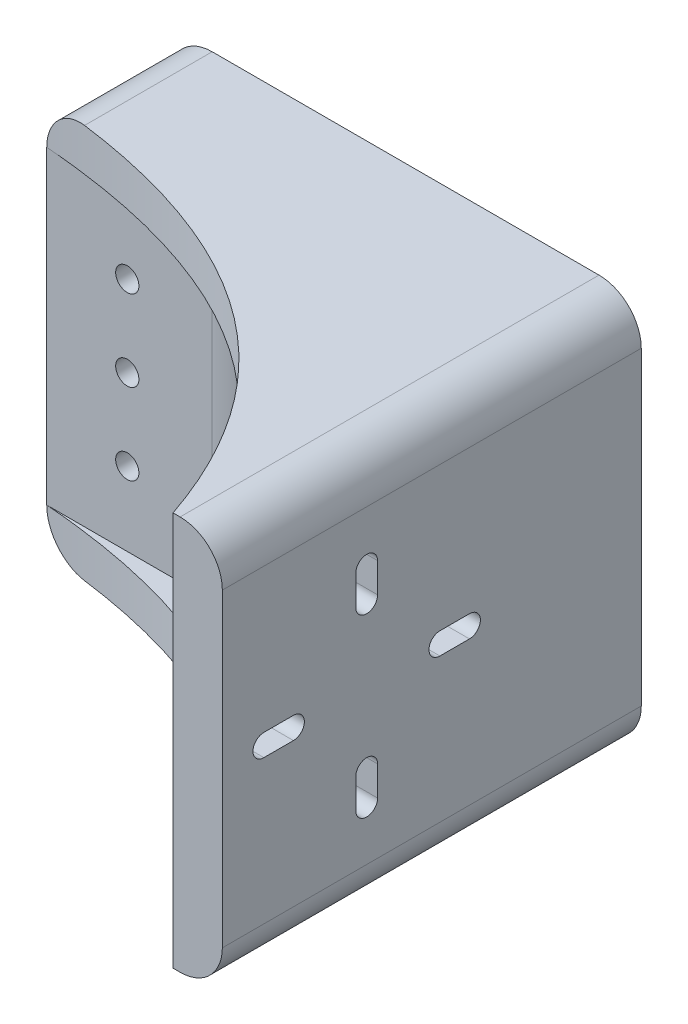
SolidWorks part; units mm, degrees
ref_plane "Plano frontal" through (0, 0, 0) normal (0, 0, 1) x (1, 0, 0)
ref_plane "Plano superior" through (0, 0, 0) normal (0, 1, 0) x (1, 0, 0)
ref_plane "Plano direito" through (0, 0, 0) normal (1, 0, 0) x (0, 0, -1)
sketch "Esboço1" plane through (0, 0, 0) normal (0, 0, 1) x (1, 0, 0)
  line L1 (-30.7631, 20.254) -> (36.1769, 20.254)
  line L2 (-30.7631, 20.254) -> (-30.7631, -19.746)
  line L3 (-30.7631, -19.746) -> (36.1769, -19.746)
  line L4 (36.1769, 20.254) -> (36.1769, -19.746)
  line L5 (2.7069, -19.746) -> (2.7069, 20.254) construction
  line L6 (-30.7631, 0.254) -> (36.1769, 0.254) construction
  point P424 (2.7069, 0.254)
  dimension "D1" = 40
  dimension "D2" = 66.94
extrude "Ressalto-extrusão1" add sketch "Esboço1" along normal blind 9.5
sketch "Esboço2" plane through (0, 0, 9.5) normal (0, 0, 1) x (1, 0, 0)
  line L5 (-30.7631, -19.746) -> (36.1769, -19.746) construction
  line L6 (29.1769, -19.746) -> (36.1769, -19.746)
  line L7 (29.1769, -19.746) -> (29.1769, 20.254)
  line L8 (29.1769, 20.254) -> (36.1769, 20.254)
  line L9 (36.1769, -19.746) -> (36.1769, 20.254)
  line L10 (32.6769, 20.254) -> (32.6769, -19.746) construction
  line L11 (29.1769, 0.254) -> (36.1769, 0.254) construction
  point P509 (32.6769, 0.254)
  dimension "D1" = 7
extrude "Ressalto-extrusão2" add sketch "Esboço2" along normal blind 50
sketch "Esboço3" plane through (0, 0, 9.5) normal (0, 0, 1) x (1, 0, 0)
  line L1 (-30.7631, -19.746) -> (-30.7631, 20.254)
  line L2 (-2.3231, 20.254) -> (-30.7631, 20.254)
  line L3 (-2.3231, -19.746) -> (-2.3231, 20.254)
  line L4 (-30.7631, -19.746) -> (-2.3231, -19.746)
  line L5 (-2.3231, 0.254) -> (-30.7631, 0.254) construction
  dimension "D2" = 28.44
  dimension "D3" = 40
extrude "Ressalto-extrusão3" add sketch "Esboço3" along normal blind 8
ref_plane "Plano1" through (0, 0.254, 0) normal (0, 1, 0) x (1, 0, 0)
sketch "Esboço4" plane through (0, -19.746, 0) normal (0, -1, 0) x (1, 0, 0)
  line L8 (-30.7631, 0) -> (36.1769, 0)
  line L9 (36.1769, 0) -> (36.1769, 59.5)
  line L10 (36.1769, 59.5) -> (29.1769, 59.5)
  line L11 (29.1769, 59.5) -> (29.1769, 9.5)
  line L12 (29.1769, 9.5) -> (-2.3231, 9.5)
  line L13 (-2.3231, 9.5) -> (-2.3231, 17.5)
  line L14 (-2.3231, 9.5) -> (-2.3231, 17.5)
  line L15 (-30.7631, 17.5) -> (-30.7631, 0)
  line L16 (-30.7631, 0) -> (36.1769, 0)
  line L17 (36.1769, 0) -> (36.1769, 59.5)
  line L18 (36.1769, 59.5) -> (29.1769, 59.5)
  line L19 (29.1769, 59.5) -> (29.1769, 9.5)
  line L20 (29.1769, 9.5) -> (-2.3231, 9.5)
  line L23 (-30.7631, 17.5) -> (-30.7631, 0)
  line L24 (-2.3231, 17.5) -> (-30.7631, 17.5)
  line L25 (-2.3231, 17.5) -> (-30.7631, 17.5)
  dimension "D1" = 0
extrude "Ressalto-extrusão4" add sketch "Esboço4" along normal blind 2 contours L16 L17 L18 L19 L20 L14 L25 L23
mirror "Espelhar1" about plane through (0, 0.254, 0) normal (0, 1, 0) of "Ressalto-extrusão4"
sketch "Esboço5" plane through (0, -21.746, 0) normal (0, -1, 0) x (1, 0, 0)
  line L8 (-30.7631, 17.5) -> (-30.7631, 0)
  line L9 (-30.7631, 0) -> (36.1769, 0)
  line L10 (36.1769, 0) -> (36.1769, 59.5)
  line L11 (36.1769, 59.5) -> (29.1769, 59.5)
  line L12 (29.1769, 59.5) -> (29.1769, 9.5)
  line L13 (29.1769, 9.5) -> (-2.3231, 9.5)
  line L14 (-2.3231, 9.5) -> (-2.3231, 17.5)
  line L15 (-2.3231, 9.5) -> (-2.3231, 17.5)
  line L16 (-30.7631, 17.5) -> (-30.7631, 0)
  line L17 (-30.7631, 0) -> (36.1769, 0)
  line L18 (36.1769, 0) -> (36.1769, 59.5)
  line L19 (36.1769, 59.5) -> (29.1769, 59.5)
  line L20 (29.1769, 59.5) -> (29.1769, 9.5)
  line L24 (-2.3231, 17.5) -> (-30.7631, 17.5)
  line L25 (-2.3231, 17.5) -> (-30.7631, 17.5)
  spline S0 degree 2 poles (29.1769, 59.5) (16.1631, 21.1433) (-30.7631, 17.5) knots 0 0 0 1 1 1
  dimension "D1" = 0
extrude "Ressalto-extrusão5" add sketch "Esboço5" along normal blind 6
mirror "Espelhar2" about plane through (0, 0.254, 0) normal (0, 1, 0) of "Ressalto-extrusão5"
fillet "Filete1" radius 5 1 edges at (-2.3231, 0.254, 17.5)
fillet "Filete2" radius 20 1 edges at (29.1769, 0.254, 9.5)
sketch "Esboço6" plane through (0, 0, 17.5) normal (0, 0, 1) x (1, 0, 0)
  line L4 (-30.7631, -21.746) -> (-7.3231, -21.746)
  line L5 (-7.3231, -21.746) -> (-7.3231, 22.254)
  line L6 (-7.3231, 22.254) -> (-30.7631, 22.254)
  line L7 (-30.7631, 22.254) -> (-30.7631, -21.746)
  line L8 (-30.7631, -21.746) -> (-7.3231, -21.746)
  line L9 (-7.3231, -21.746) -> (-7.3231, 22.254)
  line L10 (-7.3231, 22.254) -> (-30.7631, 22.254)
  line L11 (-30.7631, 22.254) -> (-30.7631, -21.746)
  circle A0 centre (-19.3231, 0.254) radius 3.625 construction
  circle A1 centre (-19.3231, 0.254) radius 3.625 construction
  circle A2 centre (-19.3231, -11.246) radius 3.625 construction
  circle A3 centre (-19.3231, -11.246) radius 3.625 construction
  circle A4 centre (-19.3231, 11.754) radius 3.625 construction
  circle A5 centre (-19.3231, 11.754) radius 3.625 construction
  circle A6 centre (-19.3231, 11.754) radius 1.65
  circle A7 centre (-19.3231, 0.254) radius 1.65
  circle A8 centre (-19.3231, -11.246) radius 1.65
  dimension "D2" = 3.3
  dimension "D1" = 0
extrude "Corte-extrusão1" cut sketch "Esboço6" against normal through all contours A6 | A7 | A8
sketch "Esboço7" plane through (0, 0, 0) normal (0, 0, -1) x (-1, 0, 0)
  line L0 (19.3231, 11.754) -> (19.3231, -11.246) construction
  line L1 (27.3231, 11.754) -> (27.3231, -11.246)
  line L2 (11.3231, 11.754) -> (11.3231, -11.246)
  arc A0 (27.3231, 11.754) -> (11.3231, 11.754) centre (19.3231, 11.754) ccw
  arc A1 (11.3231, -11.246) -> (27.3231, -11.246) centre (19.3231, -11.246) ccw
  point P2 (19.3231, 0.254)
  dimension "D1" = 8
extrude "Corte-extrusão2" cut sketch "Esboço7" against normal blind 8
fillet "Filete4" radius 6 4 edges at (36.1769, -27.746, 29.75) (36.1769, 28.254, 29.75) (-30.7631, 28.254, 8.75) (-30.7631, -27.746, 8.75)
sketch "Esboço8" plane through (36.1769, 0, 0) normal (1, 0, 0) x (0, 0, -1)
  line L0 (-39, 0.254) -> (-51.5, 0.254) construction
  line L1 (-53.6, 0.254) -> (-49.4, 0.254) construction
  line L2 (-53.6, 1.804) -> (-49.4, 1.804)
  line L3 (-53.6, -1.296) -> (-49.4, -1.296)
  line L4 (-39, -14.346) -> (-39, -10.146) construction
  line L5 (-40.55, -14.346) -> (-40.55, -10.146)
  line L6 (-37.45, -14.346) -> (-37.45, -10.146)
  line L7 (-24.4, 0.254) -> (-28.6, 0.254) construction
  line L8 (-24.4, -1.296) -> (-28.6, -1.296)
  line L9 (-24.4, 1.804) -> (-28.6, 1.804)
  line L10 (-39, 14.854) -> (-39, 10.654) construction
  line L11 (-37.45, 14.854) -> (-37.45, 10.654)
  line L12 (-40.55, 14.854) -> (-40.55, 10.654)
  circle A0 centre (-39, 0.254) radius 6 construction
  circle A1 centre (-39, 0.254) radius 6 construction
  arc A3 (-53.6, 1.804) -> (-53.6, -1.296) centre (-53.6, 0.254) ccw
  arc A4 (-49.4, -1.296) -> (-49.4, 1.804) centre (-49.4, 0.254) ccw
  arc A5 (-40.55, -14.346) -> (-37.45, -14.346) centre (-39, -14.346) ccw
  arc A6 (-37.45, -10.146) -> (-40.55, -10.146) centre (-39, -10.146) ccw
  arc A7 (-24.4, -1.296) -> (-24.4, 1.804) centre (-24.4, 0.254) ccw
  arc A8 (-28.6, 1.804) -> (-28.6, -1.296) centre (-28.6, 0.254) ccw
  arc A9 (-37.45, 14.854) -> (-40.55, 14.854) centre (-39, 14.854) ccw
  arc A10 (-40.55, 10.654) -> (-37.45, 10.654) centre (-39, 10.654) ccw
  point P6 (-51.5, 0.254)
  point P16 (-39, -12.246)
  point P23 (-26.5, 0.254)
  point P30 (-39, 12.754)
  point P35 (-39, 0.254)
  dimension "D2" = 1.55
  dimension "D3" = 4.2
  dimension "D1" = 12.5
  dimension "D4" = 4
extrude "Corte-extrusão3" cut sketch "Esboço8" against normal through all
